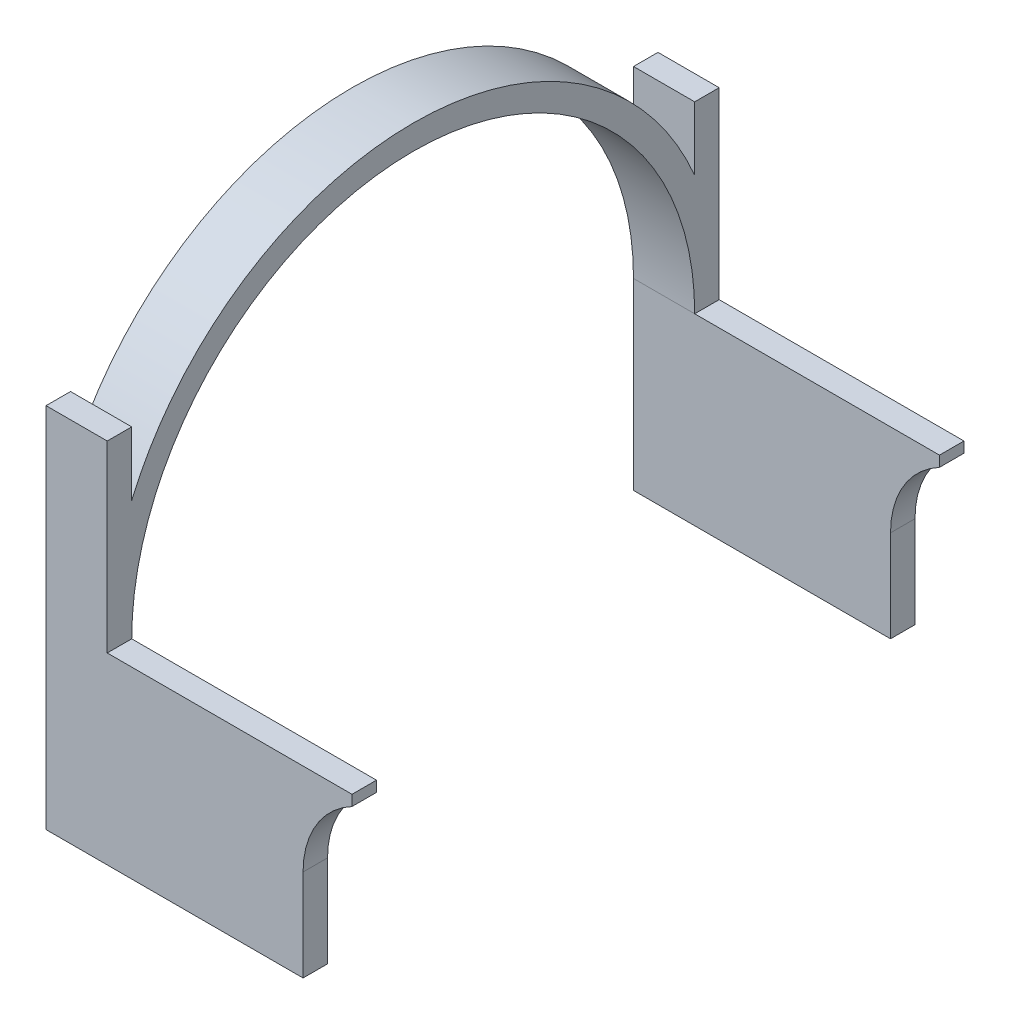
SolidWorks part; units mm, degrees
ref_plane "Front" through (0, 0, 0) normal (0, 0, 1) x (1, 0, 0)
ref_plane "Top" through (0, 0, 0) normal (0, 1, 0) x (1, 0, 0)
ref_plane "Right" through (0, 0, 0) normal (1, 0, 0) x (0, 0, -1)
sketch "草图1" plane through (0, 0, 0) normal (1, 0, 0) x (0, 0, -1)
  line L1 (0, 0) -> (0, 85.9303) construction
  line L2 (-50, 30) -> (-46, 30)
  line L3 (-50, 30) -> (-50, -30)
  line L4 (-50, -30) -> (-46, -30)
  line L5 (-46, 30) -> (-46, 19.5959)
  line L6 (46, 30) -> (50, 30)
  line L7 (46, 30) -> (46, 19.5959)
  line L8 (46, -30) -> (50, -30)
  line L9 (50, 30) -> (50, -30)
  line L10 (-46, 0) -> (-46, -30)
  line L11 (46, 0) -> (46, -30)
  arc A0 (46, 0) -> (-46, 0) centre (0, 0) ccw
  arc A1 (46, 19.5959) -> (-46, 19.5959) centre (0, 0) ccw
  dimension "D1" = 60
  dimension "D2" = 4
  dimension "D4" = 50
  dimension "D5" = 4
  dimension "D6" = 60
extrude "凸台-拉伸1" add sketch "草图1" along normal blind 10
sketch "草图2" plane through (10, 0, 0) normal (1, 0, 0) x (0, 0, -1)
  line L0 (50, -30) -> (50, 30) construction
  line L1 (-50, -30) -> (-46, -30)
  line L2 (-50, -30) -> (-50, 0)
  line L3 (-50, 0) -> (-46, 0)
  line L4 (-46, -30) -> (-46, 0)
  line L5 (46, -30) -> (50, -30)
  line L6 (46, -30) -> (46, 0)
  line L7 (46, 0) -> (50, 0)
  line L8 (50, -30) -> (50, 0)
  dimension "D1" = 30
  dimension "D2" = 30
extrude "凸台-拉伸3" add sketch "草图2" along normal blind 40
sketch "草图3" plane through (0, 0, -50) normal (0, 0, -1) x (-1, 0, 0)
  line L0 (-50, 0) -> (-50, -30) construction
  line L1 (-50, -15) -> (-90.4878, -15) construction
  line L2 (-42, -15) -> (-42, -32.2816)
  line L3 (-42, -32.2816) -> (-57, -32.2816)
  line L4 (-57, -32.2816) -> (-57, -30)
  arc A0 (-42, -15) -> (-57, -30) centre (-57, -15) ccw
  dimension "D1" = 7
extrude "切除-拉伸1" cut sketch "草图3" against normal through all
